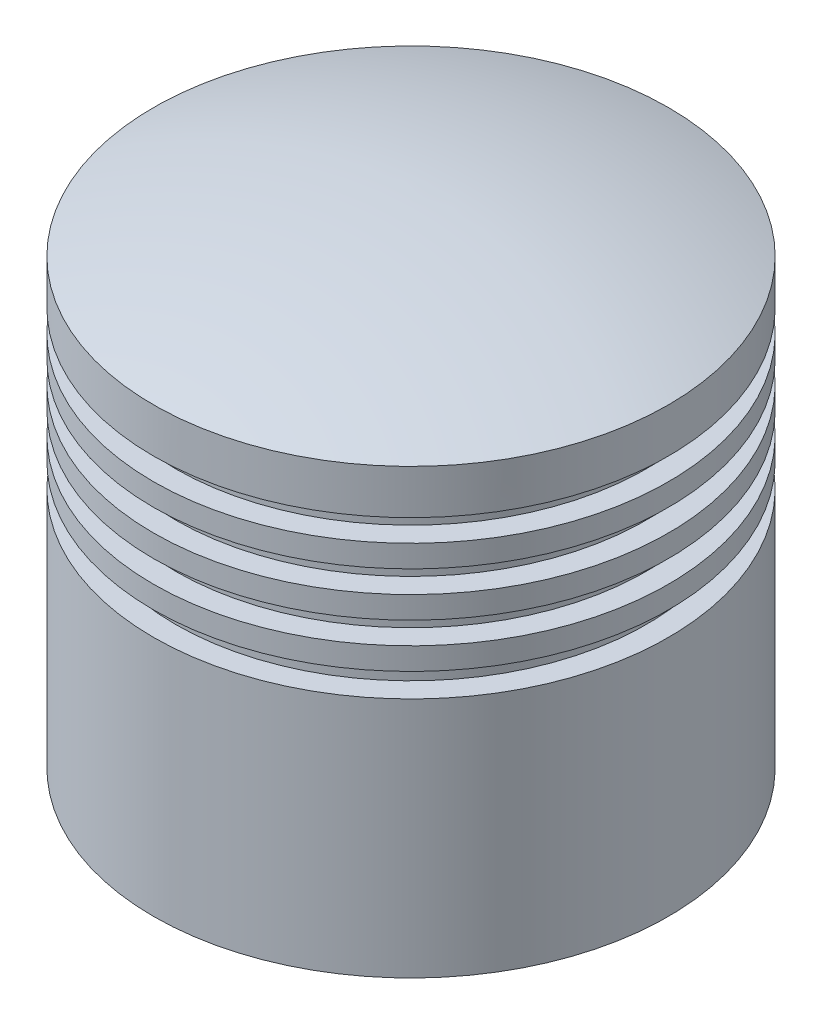
SolidWorks part; units mm, degrees
ref_plane "Front Plane" through (0, 0, 0) normal (0, 0, 1) x (1, 0, 0)
ref_plane "Top Plane" through (0, 0, 0) normal (0, 1, 0) x (1, 0, 0)
ref_plane "Right Plane" through (0, 0, 0) normal (1, 0, 0) x (0, 0, -1)
sketch "Sketch1" plane through (0, 0, 0) normal (0, 0, 1) x (1, 0, 0)
  line L0 (50, 0) -> (58, 0)
  line L1 (50, 0) -> (50, 30)
  line L2 (0, 0) -> (0, 110) construction
  line L3 (50, 30) -> (43, 30)
  line L4 (43, 30) -> (43, 97.226)
  line L5 (58, 99.7999) -> (58, 89.7999)
  line L6 (58, 89.7999) -> (53, 89.7999)
  line L7 (53, 89.7999) -> (53, 84.7999)
  line L8 (53, 84.7999) -> (58, 84.7999)
  line L9 (58, 84.7999) -> (58, 79.7999)
  line L10 (58, 79.7999) -> (53, 79.7999)
  line L11 (53, 79.7999) -> (53, 74.7999)
  line L12 (53, 74.7999) -> (58, 74.7999)
  line L13 (58, 74.7999) -> (58, 69.7999)
  line L14 (58, 69.7999) -> (53, 69.7999)
  line L15 (53, 69.7999) -> (53, 64.7999)
  line L16 (53, 64.7999) -> (58, 64.7999)
  line L18 (0, 110) -> (0, 103)
  line L19 (58, 64.7999) -> (58, 59.7999)
  line L20 (58, 59.7999) -> (53, 59.7999)
  line L21 (53, 59.7999) -> (53, 54.4378)
  line L22 (53, 54.4378) -> (58, 54.4378)
  line L23 (58, 0) -> (58, 54.4378)
  arc A0 (0, 110) -> (58, 99.7999) centre (0, -60) cw
  arc A1 (0, 103) -> (43, 97.226) centre (0, -60) cw
  point P8 (55.5, 74.7999)
  point P23 (53, 67.2999)
  dimension "D5" = 170
  dimension "D6" = 10
  dimension "D7" = 43
  dimension "D10" = 163
  dimension "D1" = 50
  dimension "D2" = 58
  dimension "D3" = 30
  dimension "D4" = 110
  dimension "D8" = 5
  dimension "D9" = 53
  dimension "D11" = 7
  dimension "D12" = 5
revolve "Revolve1" add sketch "Sketch1" angle 360 about L2
